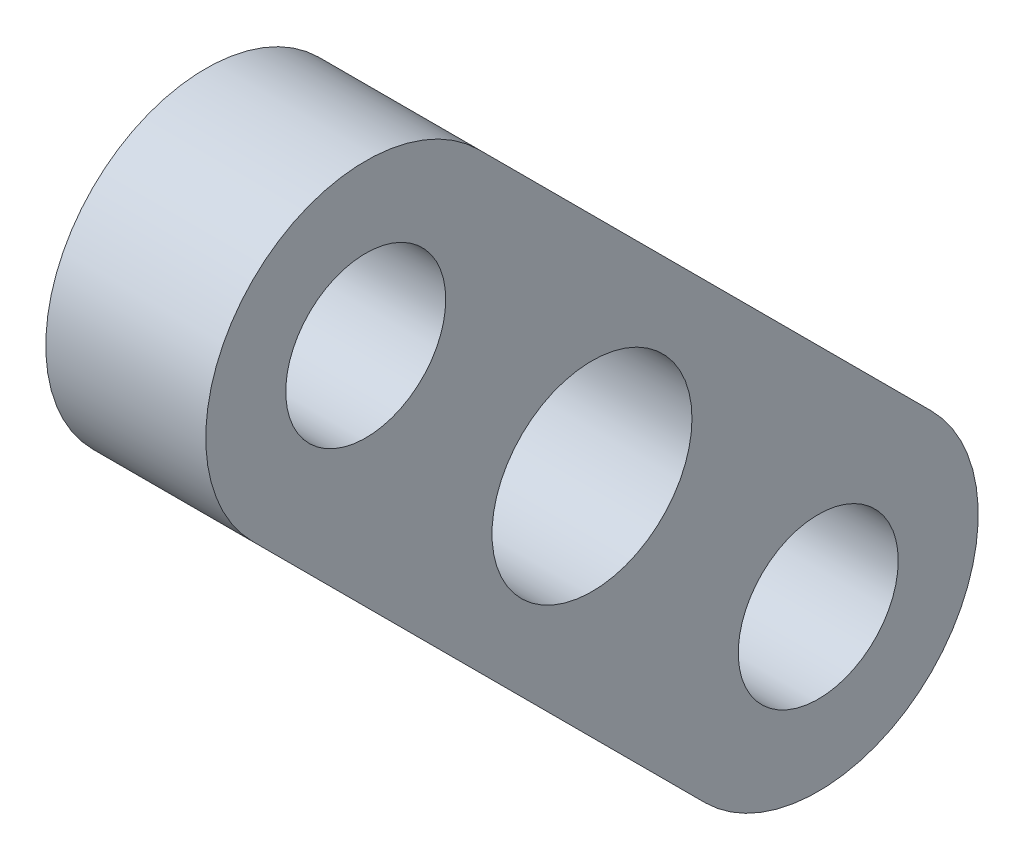
SolidWorks part; units mm, degrees
ref_plane "Front Plane" through (0, 0, 0) normal (0, 0, 1) x (1, 0, 0)
ref_plane "Top Plane" through (0, 0, 0) normal (0, 1, 0) x (1, 0, 0)
ref_plane "Right Plane" through (0, 0, 0) normal (1, 0, 0) x (0, 0, -1)
sketch "Sketch1" plane through (0, 0, 0) normal (1, 0, 0) x (0, 0, -1)
  line L0 (0, 0) -> (0, 14.3103) construction
  line L1 (-10.1168, 10.1168) -> (10.1168, -10.1168) construction
  line L2 (-4.2426, 1.4142) -> (1.4142, -4.2426)
  line L3 (-1.4142, 4.2426) -> (4.2426, -1.4142)
  circle A0 centre (0, 0) radius 4 construction
  circle A1 centre (-2.8284, 2.8284) radius 1
  circle A2 centre (2.8284, -2.8284) radius 1
  arc A3 (-1.1056, 3.8442) -> (-3.8442, 1.1056) centre (-2.8284, 2.8284) ccw
  arc A4 (1.1056, -3.8442) -> (3.8442, -1.1056) centre (2.8284, -2.8284) ccw
  circle A5 centre (0, 0) radius 1.25
  point P7 (0, 0)
  point P20 (0, 0)
  dimension "D2" = 8
  dimension "D3" = 2
  dimension "D4" = 2
  dimension "D5" = 4
  dimension "D6" = 4
  dimension "D7" = 2.5
  dimension "D1" = 45
extrude "Boss-Extrude1" add sketch "Sketch1" along normal blind 2
